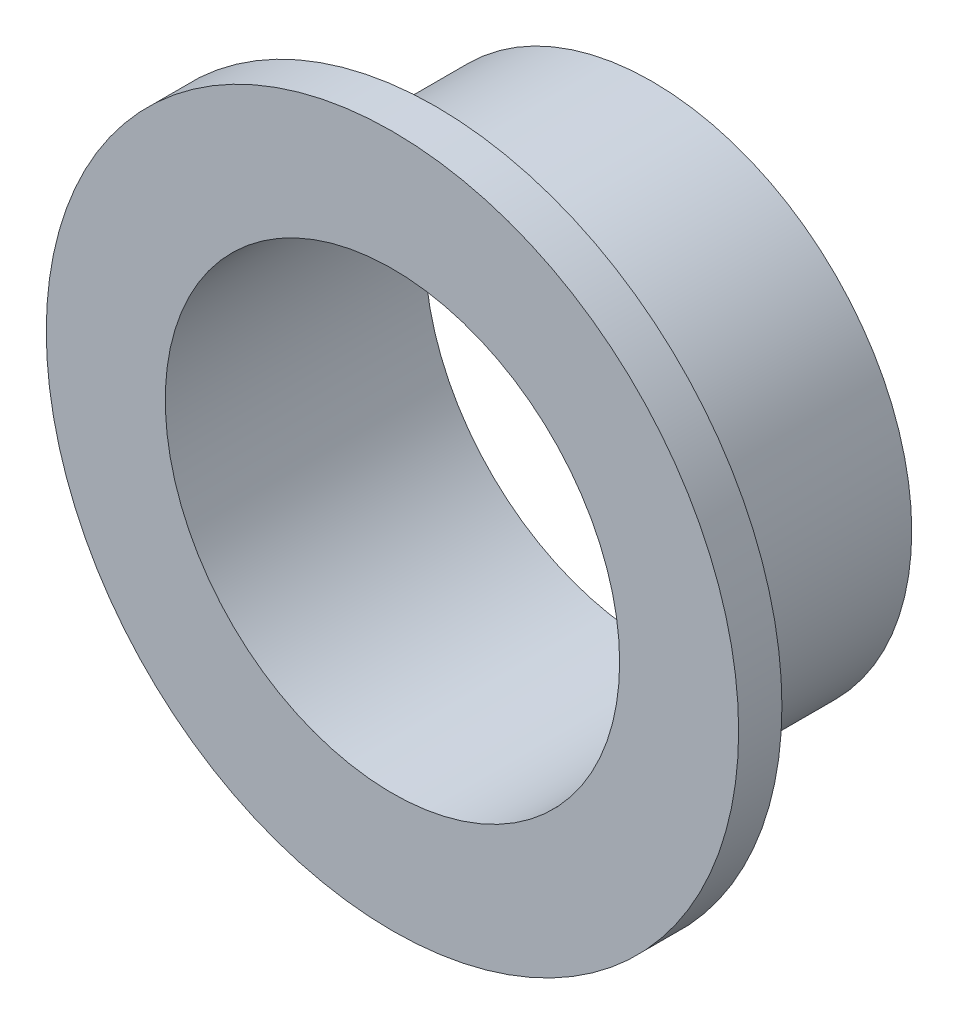
SolidWorks part; units mm, degrees
material "6061 合金"
ref_plane "前视基准面" through (0, 0, 0) normal (0, 0, 1) x (1, 0, 0)
ref_plane "上视基准面" through (0, 0, 0) normal (0, 1, 0) x (1, 0, 0)
ref_plane "右视基准面" through (0, 0, 0) normal (1, 0, 0) x (0, 0, -1)
sketch "草图1" plane through (0, 0, 0) normal (0, 0, 1) x (1, 0, 0)
  circle A0 centre (0, 0) radius 5.25
  circle A1 centre (0, 0) radius 6
  dimension "D1" = 10.5
  dimension "D2" = 12
extrude "凸台-拉伸1" add sketch "草图1" along normal blind 5
sketch "草图2" plane through (0, 0, 5) normal (0, 0, 1) x (1, 0, 0)
  circle A1 centre (0, 0) radius 5.25
  circle A2 centre (0, 0) radius 8
  dimension "D1" = 16
  dimension "D2" = 10.5
extrude "凸台-拉伸2" add sketch "草图2" along normal blind 1
